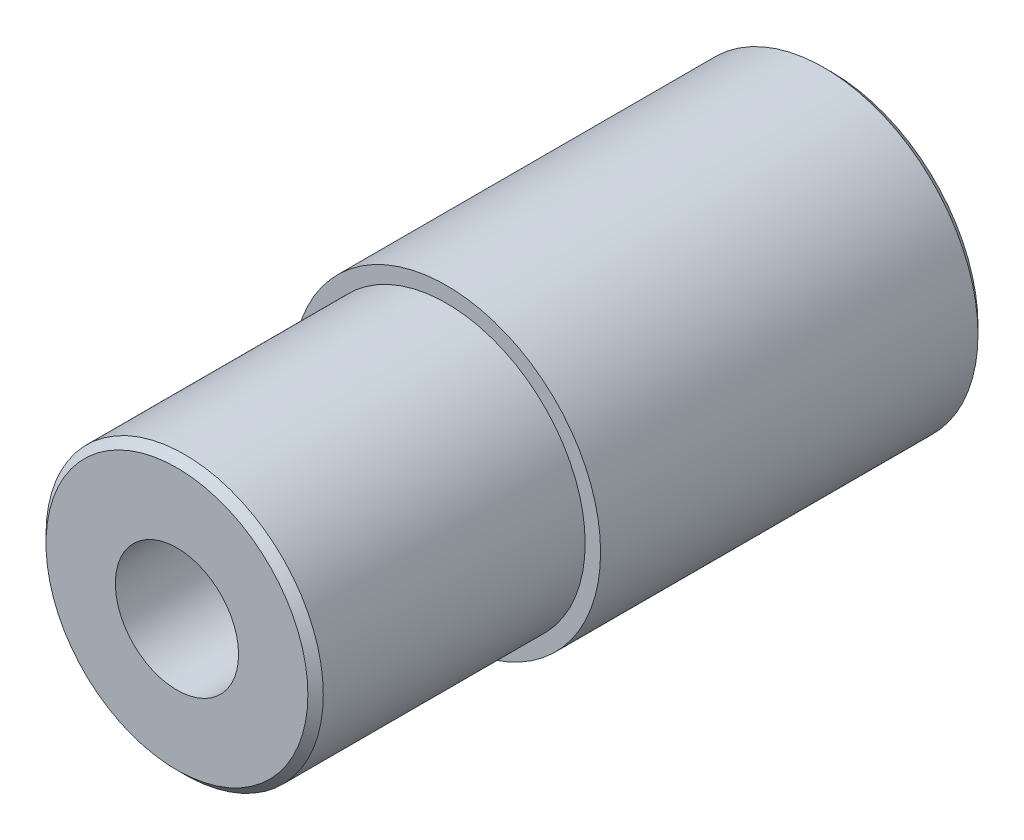
SolidWorks part; units mm, degrees
ref_plane "Alzado" through (0, 0, 0) normal (0, 0, 1) x (1, 0, 0)
ref_plane "Planta" through (0, 0, 0) normal (0, 1, 0) x (1, 0, 0)
ref_plane "Vista lateral" through (0, 0, 0) normal (1, 0, 0) x (0, 0, -1)
sketch "Croquis1" plane through (0, 0, 0) normal (0, 0, 1) x (1, 0, 0)
  circle A0 centre (0, 0) radius 20
  dimension "D1" = 40
extrude "Saliente-Extruir1" add sketch "Croquis1" along normal blind 50
sketch "Croquis2" plane through (0, 0, 50) normal (0, 0, 1) x (1, 0, 0)
  circle A0 centre (0, 0) radius 18
  dimension "D1" = 36
extrude "Saliente-Extruir2" add sketch "Croquis2" along normal blind 35
sketch "Croquis3" plane through (0, 0, 0) normal (0, 0, -1) x (-1, 0, 0)
  circle A0 centre (0, 0) radius 12.5
  dimension "D1" = 25
extrude "Cortar-Extruir1" cut sketch "Croquis3" against normal blind 28
sketch "Croquis4" plane through (0, 0, 85) normal (0, 0, 1) x (1, 0, 0)
  circle A0 centre (0, 0) radius 8
  dimension "D1" = 16
extrude "Cortar-Extruir2" cut sketch "Croquis4" against normal up to next
chamfer "Chaflán1" distance 1 angle 45 2 edges at (20, 0, 0) (18, 0, 85)
